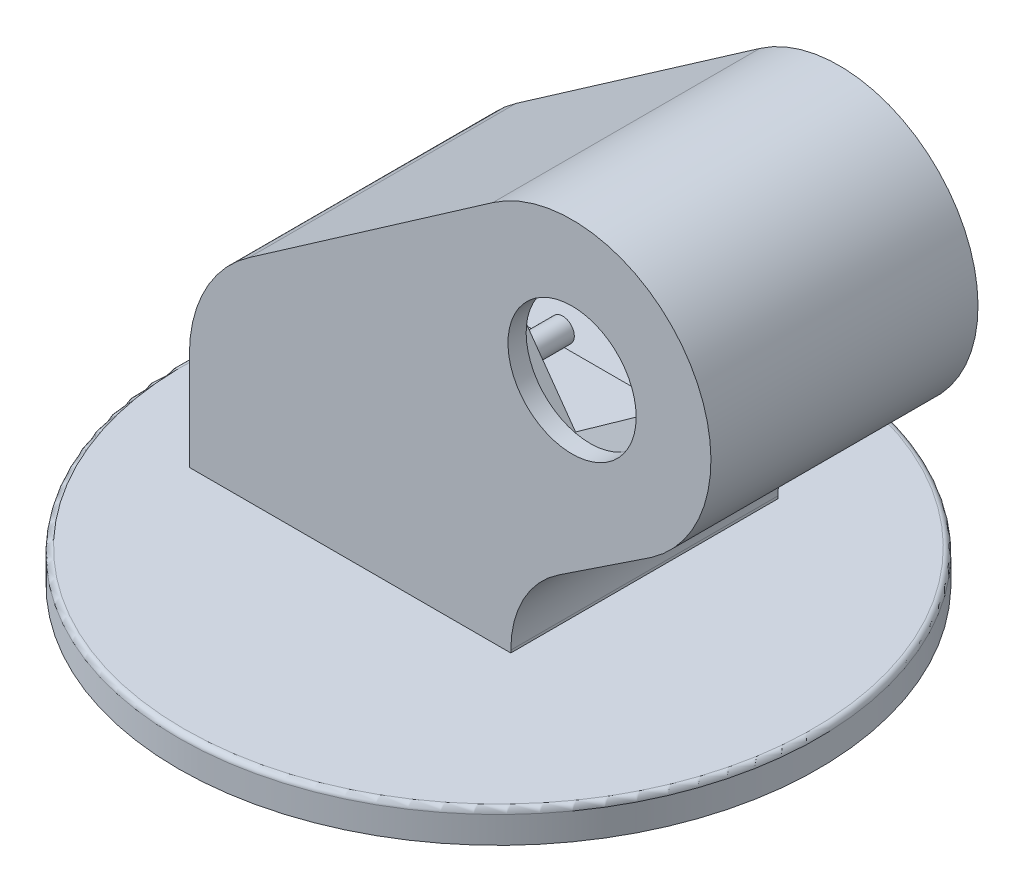
SolidWorks part; units mm, degrees
ref_plane "Front Plane" through (0, 0, 0) normal (0, 0, 1) x (1, 0, 0)
ref_plane "Top Plane" through (0, 0, 0) normal (0, 1, 0) x (1, 0, 0)
ref_plane "Right Plane" through (0, 0, 0) normal (1, 0, 0) x (0, 0, -1)
other "Configuration Table"
sketch "Sketch1" plane through (0, 0, 0) normal (0, 1, 0) x (1, 0, 0)
  circle A0 centre (0, 0) radius 29.95
  dimension "D1" = 59.9
extrude "Boss-Extrude1" add sketch "Sketch1" along normal blind 3
fillet "Fillet1" radius 0.5 1 edges at (0, 3, 29.95)
sketch "Sketch3" plane through (0, 0, 0) normal (0, 0, 1) x (1, 0, 0)
  line L0 (22.3196, 17.3268) -> (13.6344, 11.5669)
  line L5 (29.45, 3) -> (-29.45, 3) construction
  line L6 (7.476, 38.6732) -> (-15.3518, 22.7995)
  line L7 (7.476, 38.6732) -> (22.3196, 17.3268) construction
  line L8 (9.1612, 3.233) -> (9.1612, 3)
  line L9 (-20.93, 12.1263) -> (-20.93, 3)
  line L10 (-20.93, 3) -> (9.1612, 3)
  circle A1 centre (14.8978, 28) radius 6
  arc A2 (-15.3518, 22.7995) -> (-20.93, 12.1263) centre (-7.93, 12.1263) ccw
  arc A3 (21.8425, 17.0104) -> (7.476, 38.6732) centre (14.8978, 28) ccw
  arc A4 (13.6344, 11.5669) -> (9.1612, 3.233) centre (19.1612, 3.233) ccw
  dimension "D1" = 12
  dimension "D2" = 26
  dimension "D3" = 26
  dimension "D5" = 10
  dimension "D4" = 25
extrude "Boss-Extrude2" add sketch "Sketch3" against normal blind 17 and the other way blind 8 contours L7 L6 A2 L9 L10 L8 A4 L0 A1 | A3 L7 A1
sketch "Sketch5" plane through (0, 0, -17) normal (0, 0, -1) x (-1, 0, 0)
  line L0 (-8.6265, 37.0372) -> (14.43, 21.0372)
  line L1 (-20.8583, 18.7548) -> (-10.8264, 12.2872)
  line L2 (19.1587, 12) -> (19.1587, 5.2622)
  line L3 (-7.1612, 5.5634) -> (-7.1612, 5.2622)
  line L12 (-7.1612, 5.2622) -> (19.1587, 5.2622)
  arc A2 (-8.6265, 37.0372) -> (-20.8583, 18.7548) centre (-14.8978, 28) ccw
  arc A4 (-10.8264, 12.2872) -> (-7.1612, 5.5634) centre (-15.1612, 5.5634) cw
  arc A7 (19.1587, 12) -> (14.43, 21.0372) centre (8.1587, 12) ccw
  dimension "D1" = 22
  dimension "D2" = 22
  dimension "D3" = 8
extrude "Cut-Extrude2" cut sketch "Sketch5" against normal blind 14.3
sketch "Sketch4" plane through (0, 0, -17) normal (0, 0, -1) x (-1, 0, 0)
  line L0 (-23.2616, 26.5886) -> (-4.5238, 13.2509)
  line L1 (-23.2616, 26.5886) -> (-16.3028, 36.3649)
  line L2 (-4.5238, 13.2509) -> (2.435, 23.0272)
  line L3 (-16.3028, 36.3649) -> (2.435, 23.0272)
  line L4 (-23.2616, 26.5886) -> (2.435, 23.0272) construction
  line L5 (-4.5238, 13.2509) -> (-16.3028, 36.3649) construction
  line L6 (-14.8978, 28) -> (-14.8978, 41) construction
  arc A0 (-7.476, 38.6732) -> (-22.3196, 17.3268) centre (-14.8978, 28) ccw construction
  arc A3 (-8.6265, 37.0372) -> (-20.8583, 18.7548) centre (-14.8978, 28) ccw construction
  point P1 (-10.4133, 24.8079)
  point P14 (-24.0403, 34.1168)
  dimension "D2" = 5
extrude "Cut-Extrude4" cut sketch "Sketch4" against normal blind 9 from surface at -14.3 starting at face at (8.8978, 28, -2.7)
sketch "Sketch7" plane through (0, 0, -2.7) normal (0, 0, -1) x (-1, 0, 0)
  circle A0 centre (-21.489, 32.6916) radius 1.0925
  circle A1 centre (0.6841, 16.9552) radius 1.0925
  dimension "D1" = 2.185
  dimension "D2" = 2.185
extrude "Boss-Extrude3" add sketch "Sketch7" along normal blind 4
sketch "Sketch8" plane through (0, 0, 0) normal (0, -1, 0) x (1, 0, 0)
  line L0 (4.8805, 3.4931) -> (-14.9, 2.25)
  line L5 (4.8805, -3.4931) -> (-14.9, -2.25)
  line L6 (-15.1634, 4.2418) -> (5.1, 5.5)
  line L7 (-15.2255, 2.2263) -> (-15.4241, -4.2176) construction
  line L8 (5.1, 3.5) -> (5.1, -3.5) construction
  line L9 (-15.4241, -4.2176) -> (5.1, -5.5)
  arc A0 (4.4153, -5.4572) -> (4.4196, 5.4578) centre (5.1, 0) ccw
  arc A3 (4.8805, -3.4931) -> (4.8805, 3.4931) centre (5.1, 0) ccw
  arc A4 (-14.9, 2.25) -> (-14.9, -2.25) centre (-14.9, 0) ccw
  arc A5 (-15.1634, 4.2418) -> (-14.905, -4.25) centre (-14.9, 0) ccw
extrude "Boss-Extrude4" add sketch "Sketch8" along normal blind 2 contours L6 A5 L9 A0 A4 L0 A3 L5
